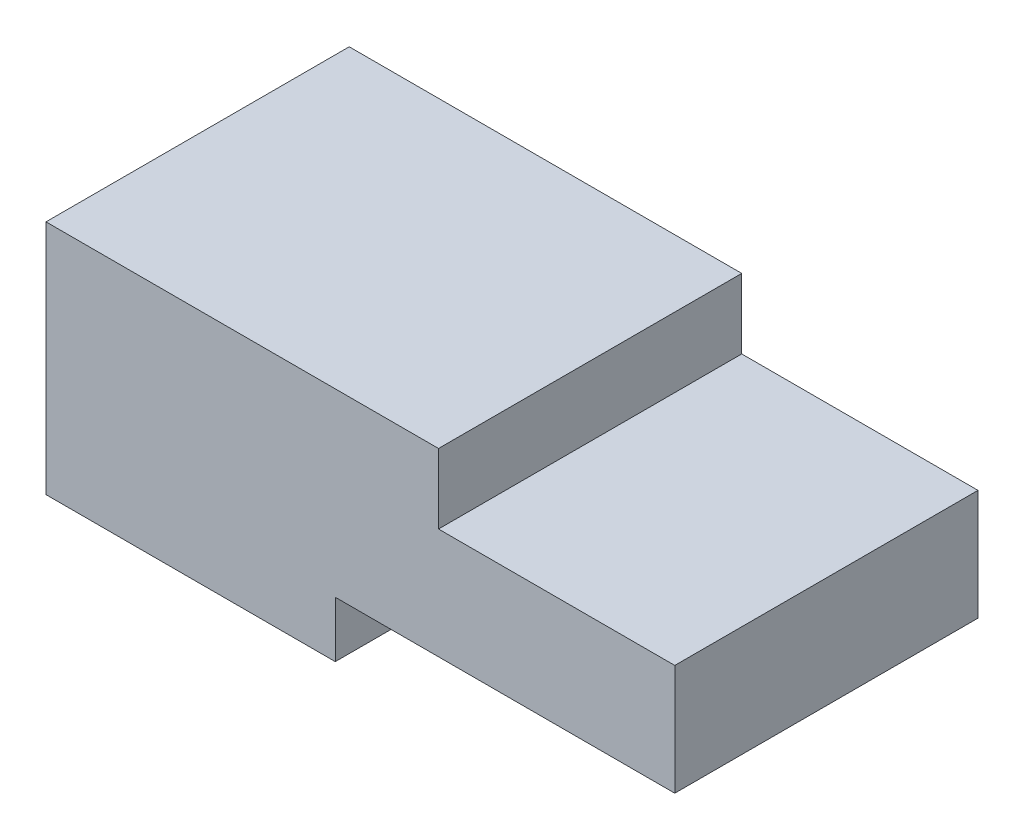
SolidWorks part; units mm, degrees
ref_plane "Front Plane" through (0, 0, 0) normal (0, 0, 1) x (1, 0, 0)
ref_plane "Top Plane" through (0, 0, 0) normal (0, 1, 0) x (1, 0, 0)
ref_plane "Right Plane" through (0, 0, 0) normal (1, 0, 0) x (0, 0, -1)
sketch "Sketch1" plane through (0, 0, 0) normal (0, 1, 0) x (1, 0, 0)
  line L1 (0, 0) -> (33.8, 0)
  line L2 (0, 0) -> (0, 16.3)
  line L3 (0, 16.3) -> (33.8, 16.3)
  line L4 (33.8, 0) -> (33.8, 16.3)
  dimension "D1" = 33.8
  dimension "D2" = 16.3
extrude "Boss-Extrude1" add sketch "Sketch1" against normal blind 12.7
sketch "Sketch2" plane through (0, 0, 0) normal (0, 0, 1) x (1, 0, 0)
  line L0 (0, -12.7) -> (33.8, -12.7) construction
  line L1 (15.55, -12.7) -> (33.8, -12.7)
  line L2 (15.55, -12.7) -> (15.55, -9.7)
  line L3 (15.55, -9.7) -> (33.8, -9.7)
  line L4 (33.8, -12.7) -> (33.8, -9.7)
  line L5 (33.8, -12.7) -> (33.8, 0) construction
  line L6 (0, 0) -> (33.8, 0) construction
  line L7 (21.1, 0) -> (33.8, 0)
  line L8 (21.1, 0) -> (21.1, -3.75)
  line L9 (21.1, -3.75) -> (33.8, -3.75)
  line L10 (33.8, 0) -> (33.8, -3.75)
  dimension "D1" = 3
  dimension "D2" = 3.75
  dimension "D3" = 18.25
  dimension "D4" = 12.7
extrude "Cut-Extrude1" cut sketch "Sketch2" against normal through all
